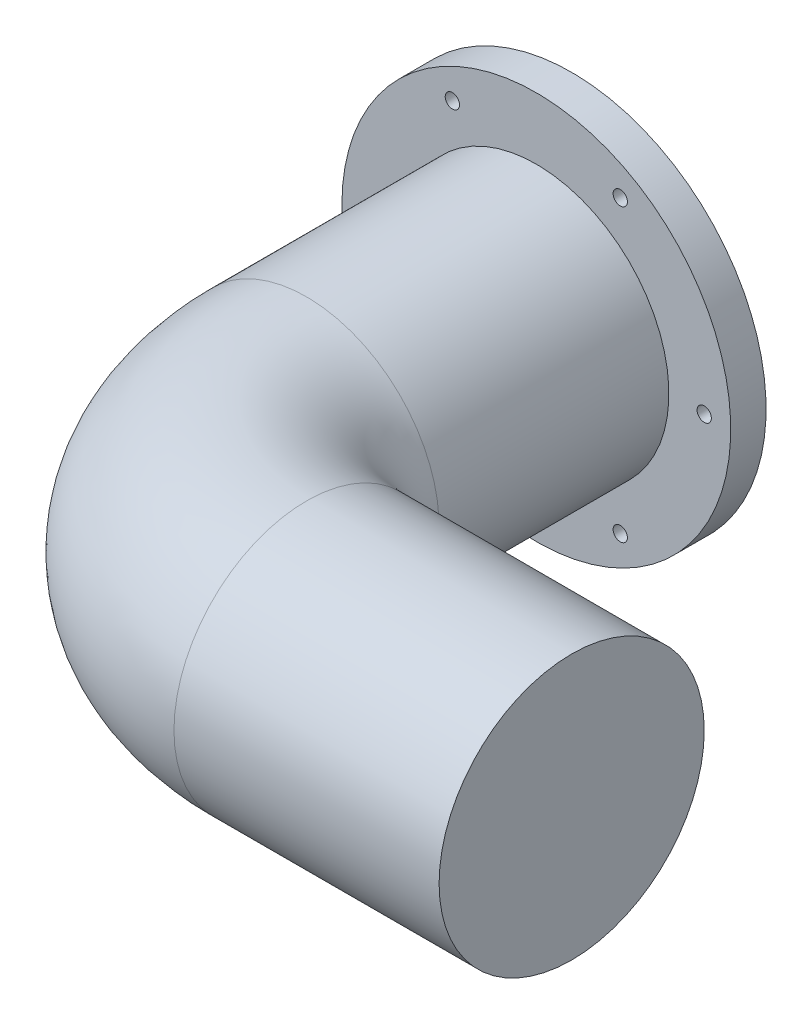
SolidWorks part; units mm, degrees
material "Plain Carbon Steel"
ref_plane "Front Plane" through (0, 0, 0) normal (0, 0, 1) x (1, 0, 0)
ref_plane "Top Plane" through (0, 0, 0) normal (0, 1, 0) x (1, 0, 0)
ref_plane "Right Plane" through (0, 0, 0) normal (1, 0, 0) x (0, 0, -1)
sketch "Sketch1" plane through (0, 0, 0) normal (0, 1, 0) x (1, 0, 0)
  line L0 (0, 0) -> (-75, 0)
  line L1 (-125, 50) -> (-125, 125)
  arc A0 (-75, 0) -> (-125, 50) centre (-75, 50) cw
  dimension "D1" = 75
  dimension "D2" = 75
  dimension "D3" = 50
  dimension "D4" = 50
sweep "Sweep1" add path "Sketch1" circular profile diameter 75 parameters "D3"=75
sketch "Sketch3" plane through (0, 0, -125) normal (0, 0, -1) x (-1, 0, 0)
  circle A0 centre (125, 0) radius 55
  circle A1 centre (125, 0) radius 37.5 construction
  dimension "D1" = 110
extrude "Boss-Extrude1" add sketch "Sketch3" against normal blind 10
sketch "Sketch4" plane through (0, 0, -115) normal (0, 0, 1) x (1, 0, 0)
  circle A0 centre (-125, 0) radius 47.5 construction
  circle A1 centre (-125, 0) radius 37.5 construction
  point P5 (-148.75, 41.1362)
  point P11 (-125, 0)
  point P12 (-101.25, 41.1362)
  point P13 (-77.5, 0)
  point P14 (-101.25, -41.1362)
  point P15 (-148.75, -41.1362)
  point P16 (-172.5, 0)
  point P17 (-125, 0)
  dimension "D1" = 95
hole_wizard "Tap Drill for #10-32 Tap1" positions "Sketch8" profile "Sketch10" hole size "#10-32" standard "ANSI Inch"
sketch "Sketch8" plane through (0, 0, -115) normal (0, 0, 1) x (1, 0, 0)
  point P12 (-148.75, 41.1362)
  point P15 (-172.5, 0)
  point P18 (-148.75, -41.1362)
  point P21 (-101.25, -41.1362)
  point P24 (-77.5, 0)
  point P27 (-101.25, 41.1362)
  point P34 (0, 0)
  point P35 (0, 0)
  point P36 (0, 0)
  point P37 (0, 0)
sketch "Sketch10" plane through (-148.75, 41.1362, -115) normal (1, 0, 0) x (0, -1, 0)
  line L0 (0, 0) -> (0, 10)
  line L1 (0, 10) -> (2.0193, 10)
  line L2 (2.0193, 10) -> (2.0193, 0)
  line L5 (2.0193, 0) -> (0, 0)
  line L11 (0, -6.35) -> (0, 107.95) construction
  dimension "Thru Hole Dia." = 4.0386
  dimension "Thru Hole Depth" = 10
sketch "Sketch11" plane through (0, 0, -125) normal (0, 0, -1) x (-1, 0, 0)
  line L0 (125, 0) -> (152.5, 0) construction
  line L1 (146.8172, 16.7409) -> (125, 0) construction
  circle A0 centre (125, 0) radius 27.5 construction
  circle A1 centre (125, 0) radius 55 construction
  circle A2 centre (146.8172, 16.7409) radius 7
  circle A3 centre (122.4149, 27.3782) radius 7
  circle A4 centre (100.4349, 12.3615) radius 7
  circle A5 centre (101.473, -14.2383) radius 7
  circle A6 centre (124.5564, -27.4964) radius 7
  circle A7 centre (148.0555, -14.9897) radius 7
  point P4 (146.8172, 16.7409)
  point P5 (122.4149, 27.3782)
  point P6 (100.4349, 12.3615)
  point P7 (124.5564, -27.4964)
  point P8 (148.0555, -14.9897)
  point P9 (101.473, -14.2383)
  dimension "D6" = 55
  dimension "D8" = 14
  dimension "D1" = 26.62
  dimension "D2" = 26.62
  dimension "D3" = 26.62
  dimension "D4" = 26.62
  dimension "D5" = 26.62
  dimension "D7" = 37.5
extrude "Cut-Extrude1" cut sketch "Sketch11" against normal blind 5
equation "\"GEARDIST\"=26.62"
equation "\"D1@Sketch11\"=\"GEARDIST\""
equation "\"D2@Sketch11\"=\"GEARDIST\""
equation "\"D3@Sketch11\"=\"GEARDIST\""
equation "\"D4@Sketch11\"=\"GEARDIST\""
equation "\"D5@Sketch11\"=\"GEARDIST\""
